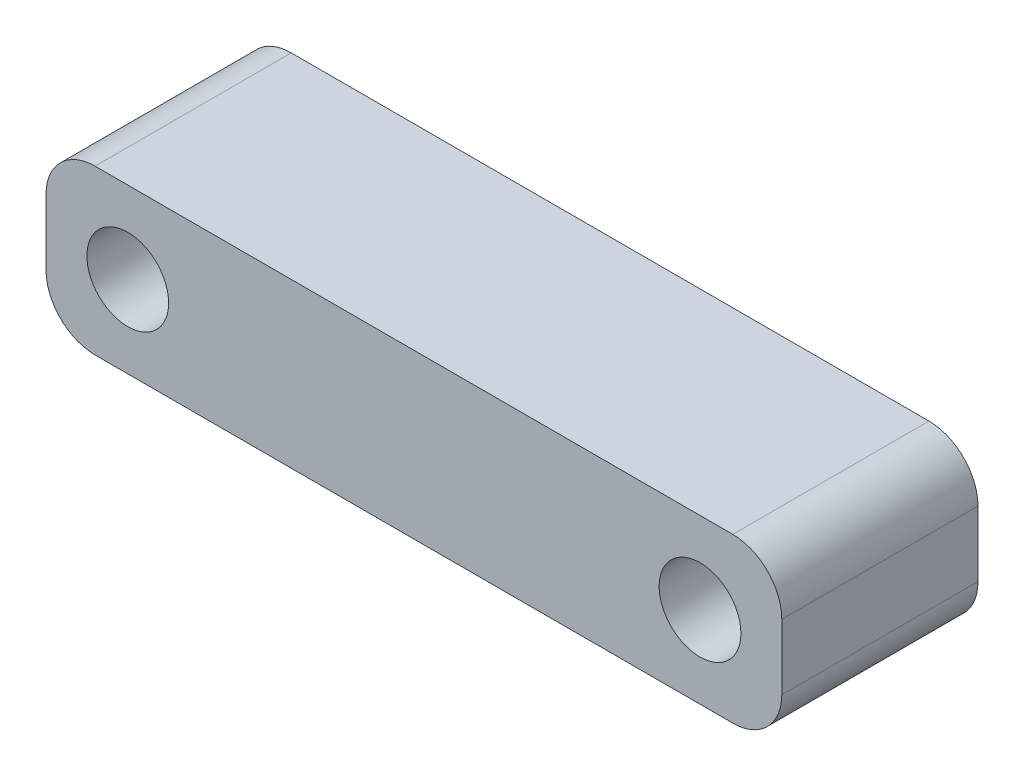
SolidWorks part; units mm, degrees
ref_plane "Front Plane" through (0, 0, 0) normal (0, 0, 1) x (1, 0, 0)
ref_plane "Top Plane" through (0, 0, 0) normal (0, 1, 0) x (1, 0, 0)
ref_plane "Right Plane" through (0, 0, 0) normal (1, 0, 0) x (0, 0, -1)
sketch "Sketch1" plane through (0, 0, 0) normal (0, 0, 1) x (1, 0, 0)
  line L0 (0, 0) -> (35, 0) construction
  line L2 (-2, 5) -> (37, 5)
  line L3 (-5, 2) -> (-5, -2)
  line L4 (-2, -5) -> (37, -5)
  line L5 (40, 2) -> (40, -2)
  circle A0 centre (0, 0) radius 2.5
  circle A1 centre (35, 0) radius 2.5
  arc A2 (37, 5) -> (40, 2) centre (37, 2) cw
  arc A3 (37, -5) -> (40, -2) centre (37, -2) ccw
  arc A4 (-5, -2) -> (-2, -5) centre (-2, -2) ccw
  arc A5 (-2, 5) -> (-5, 2) centre (-2, 2) ccw
  dimension "D1" = 5
  dimension "D2" = 5
  dimension "D8" = 3
  dimension "D3" = 35
  dimension "D4" = 5
  dimension "D5" = 5
  dimension "D6" = 5
  dimension "D7" = 5
extrude "Boss-Extrude1" add sketch "Sketch1" along normal blind 12
